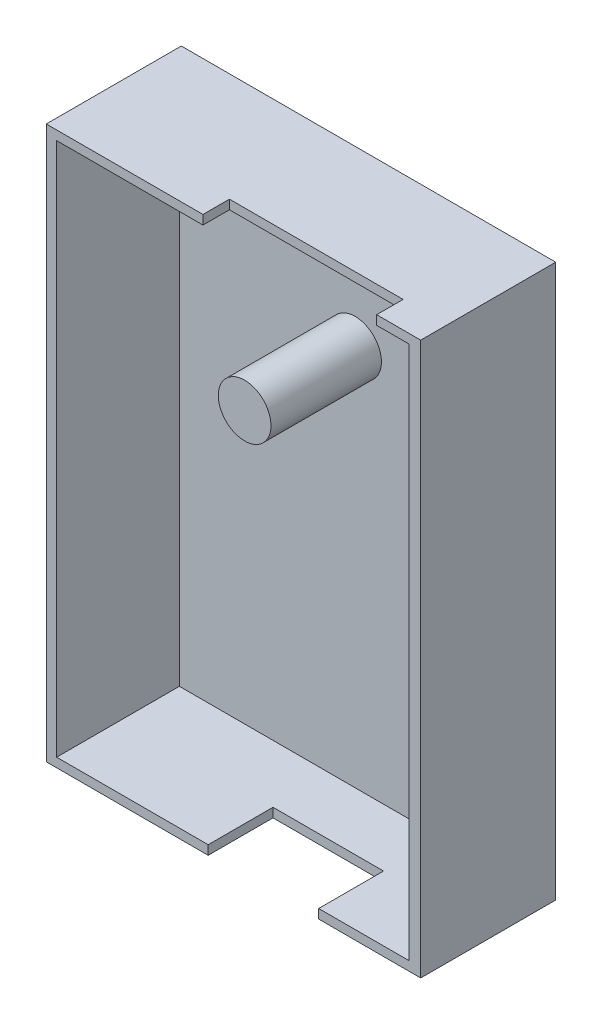
SolidWorks part; units mm, degrees
ref_plane "Piano frontale" through (0, 0, 0) normal (0, 0, 1) x (1, 0, 0)
ref_plane "Piano superiore" through (0, 0, 0) normal (0, 1, 0) x (1, 0, 0)
ref_plane "Piano destro" through (0, 0, 0) normal (1, 0, 0) x (0, 0, -1)
sketch "Schizzo1" plane through (0, 0, 0) normal (0, 0, 1) x (1, 0, 0)
  line L0 (-21.0839, 26.2762) -> (39.9161, 26.2762)
  line L1 (39.9161, 26.2762) -> (39.9161, -63.7238)
  line L2 (39.9161, -63.7238) -> (-21.0839, -63.7238)
  line L3 (-21.0839, -63.7238) -> (-21.0839, 26.2762)
  dimension "D1" = 90
  dimension "D2" = 61
extrude "Estrusione-Estrusione1" add sketch "Schizzo1" along normal blind 22
sketch "Schizzo2" plane through (0, 0, 22) normal (0, 0, 1) x (1, 0, 0)
  line L0 (-19.3948, 24.7768) -> (38.0374, 24.7768)
  line L1 (38.0374, 24.7768) -> (38.0374, -62.2244)
  line L2 (38.0374, -62.2244) -> (-19.3948, -62.2244)
  line L3 (-19.3948, -62.2244) -> (-19.3948, 24.7768)
extrude "Taglio-Estrusione1" cut sketch "Schizzo2" against normal blind 20
sketch "Schizzo3" plane through (0, 0, 2) normal (0, 0, 1) x (1, 0, 0)
  circle A0 centre (9.2338, 0) radius 4.2881
  point P2 (0, 0)
extrude "Estrusione-Estrusione3" add sketch "Schizzo3" along normal blind 18
sketch "Schizzo4" plane through (0, -63.7238, 0) normal (0, -1, 0) x (-1, 0, 0)
  line L0 (-5.2963, -11.4381) -> (-23.2963, -11.4381)
  line L1 (-23.2963, -11.4381) -> (-23.2963, -25.4381)
  line L2 (-23.2963, -25.4381) -> (-5.2963, -25.4381)
  line L3 (-5.2963, -25.4381) -> (-5.2963, -11.4381)
  dimension "D1" = 18
  dimension "D2" = 14
extrude "Taglio-Estrusione2" cut sketch "Schizzo4" against normal blind 4
sketch "Schizzo5" plane through (0, 26.2762, 0) normal (0, 1, 0) x (1, 0, 0)
  line L0 (4.4454, -17.6878) -> (32.7385, -17.6878)
  line L1 (32.7385, -17.6878) -> (32.7385, -25.547)
  line L2 (32.7385, -25.547) -> (4.4454, -25.547)
  line L3 (4.4454, -25.547) -> (4.4454, -17.6878)
extrude "Taglio-Estrusione4" cut sketch "Schizzo5" against normal blind 4
sketch "Schizzo9" plane through (0, 0, 22) normal (0, 0, 1) x (1, 0, 0)
